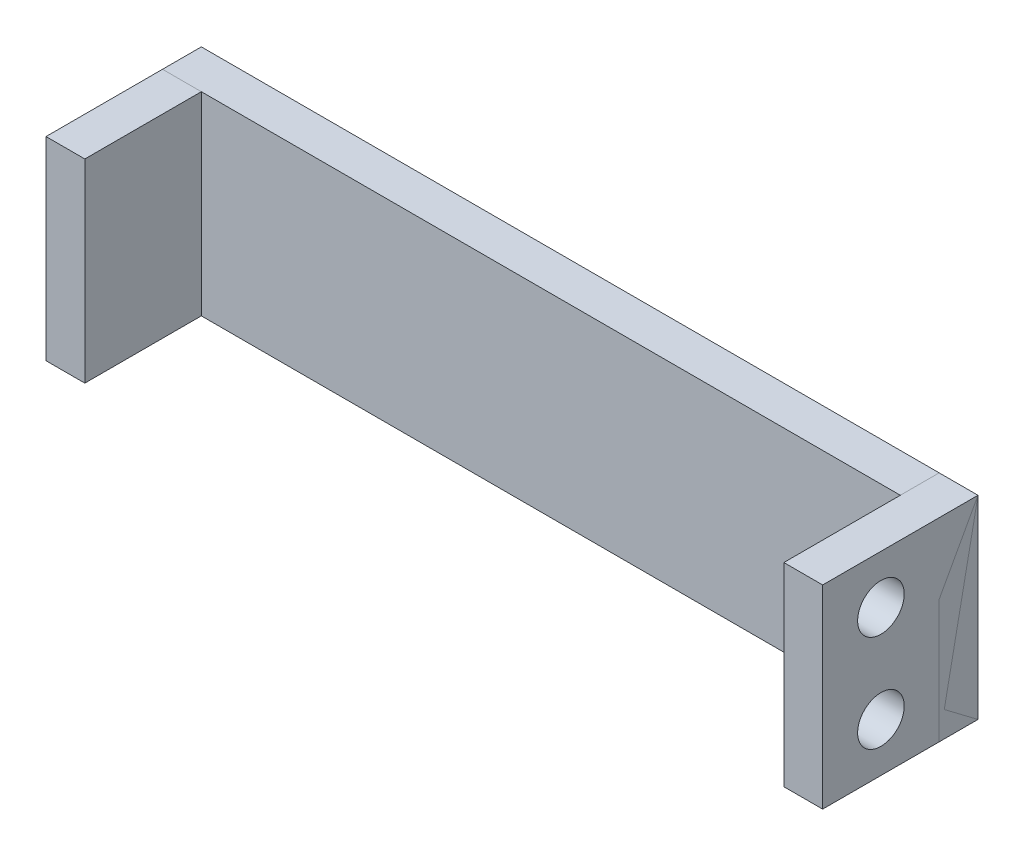
SolidWorks part; units mm, degrees
ref_plane "Front Plane" through (0, 0, 0) normal (0, 0, 1) x (1, 0, 0)
ref_plane "Top Plane" through (0, 0, 0) normal (0, 1, 0) x (1, 0, 0)
ref_plane "Right Plane" through (0, 0, 0) normal (1, 0, 0) x (0, 0, -1)
sketch "Sketch2" plane through (0, 0, 0) normal (1, 0, 0) x (0, 0, -1)
  line L1 (0, 0) -> (10.16, 0)
  line L2 (0, 0) -> (0, 12.7)
  line L3 (0, 12.7) -> (10.16, 12.7)
  line L4 (10.16, 0) -> (10.16, 12.7)
  circle A0 centre (3.81, 9.525) radius 1.524
  circle A1 centre (3.81, 3.175) radius 1.524
  dimension "D3" = 3.048
  dimension "D4" = 3.048
  dimension "D1" = 10.16
  dimension "D2" = 12.7
  dimension "D5" = 6.35
  dimension "D6" = 3.175
  dimension "D7" = 3.81
  dimension "0.2" = 3.81
extrude "Boss-Extrude2" add sketch "Sketch2" along normal blind 2.54
sketch "Sketch3" plane through (2.54, 0, 0) normal (1, 0, 0) x (0, 0, -1)
  line L0 (10.16, 0) -> (10.16, 12.7) construction
  line L1 (7.62, 12.7) -> (10.16, 12.7)
  line L2 (7.62, 12.7) -> (7.62, 0)
  line L3 (7.62, 0) -> (10.16, 0)
  line L4 (10.16, 12.7) -> (10.16, 0)
  line L5 (10.16, 12.7) -> (0, 12.7) construction
  dimension "D1" = 2.54
extrude "Boss-Extrude3" add sketch "Sketch3" against normal blind 50.8 separate body
sketch "Sketch4" plane through (-48.26, 0, 0) normal (-1, 0, 0) x (0, 0, 1)
  line L1 (-10.16, 12.7) -> (0, 12.7)
  line L2 (-10.16, 12.7) -> (-10.16, 0)
  line L3 (-10.16, 0) -> (0, 0)
  line L4 (0, 12.7) -> (0, 0)
extrude "Boss-Extrude4" add sketch "Sketch4" against normal blind 2.54 separate body
